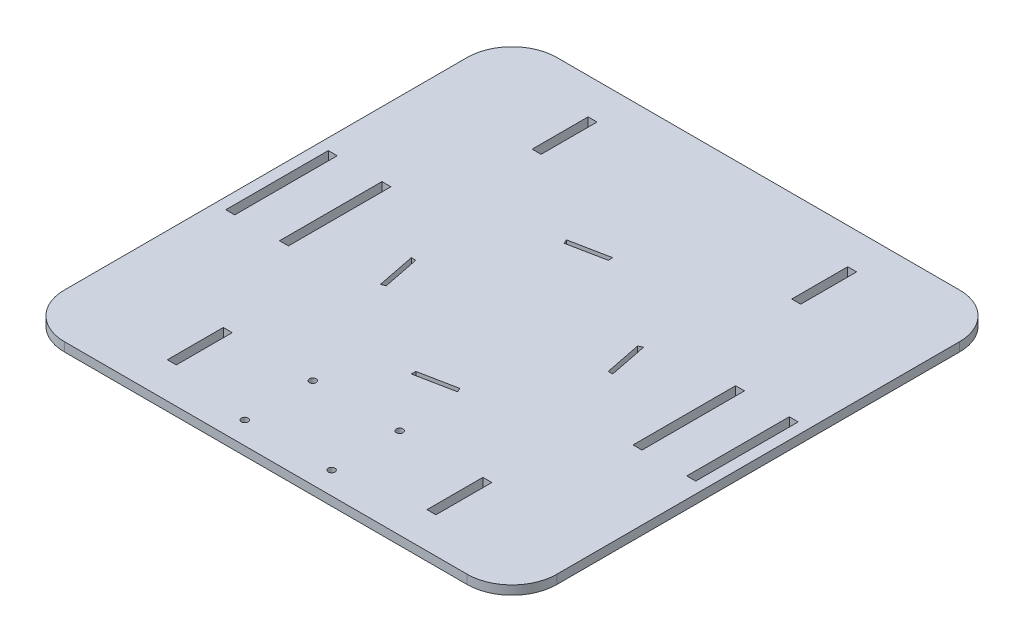
SolidWorks part; units mm, degrees
ref_plane "Front Plane" through (0, 0, 0) normal (0, 0, 1) x (1, 0, 0)
ref_plane "Top Plane" through (0, 0, 0) normal (0, 1, 0) x (1, 0, 0)
ref_plane "Right Plane" through (0, 0, 0) normal (1, 0, 0) x (0, 0, -1)
sketch "Sketch1" plane through (0, 0, 0) normal (0, 1, 0) x (1, 0, 0)
  line L1 (0, 0) -> (279.4, 0)
  line L2 (0, 0) -> (0, 279.4)
  line L3 (0, 279.4) -> (279.4, 279.4)
  line L4 (279.4, 0) -> (279.4, 279.4)
  dimension "D1" = 279.4
  dimension "D2" = 279.4
extrude "Boss-Extrude1" add sketch "Sketch1" along normal blind 5.08
fillet "Fillet1" radius 25.4 4 edges at (0, 2.54, -279.4) (0, 2.54, 0) (279.4, 2.54, 0) (279.4, 2.54, -279.4)
sketch "Sketch2" plane through (0, 5.08, 0) normal (0, 1, 0) x (1, 0, 0)
  line L0 (254, 279.4) -> (25.4, 279.4) construction
  line L1 (63.5, 259.08) -> (68.58, 259.08)
  line L2 (63.5, 259.08) -> (63.5, 227.33)
  line L3 (63.5, 227.33) -> (68.58, 227.33)
  line L4 (68.58, 259.08) -> (68.58, 227.33)
  line L5 (210.82, 259.08) -> (215.9, 259.08)
  line L6 (210.82, 259.08) -> (210.82, 227.33)
  line L7 (210.82, 227.33) -> (215.9, 227.33)
  line L8 (215.9, 259.08) -> (215.9, 227.33)
  line L9 (63.5, 52.07) -> (68.58, 52.07)
  line L10 (63.5, 52.07) -> (63.5, 20.32)
  line L11 (63.5, 20.32) -> (68.58, 20.32)
  line L12 (68.58, 52.07) -> (68.58, 20.32)
  line L13 (210.82, 52.07) -> (215.9, 52.07)
  line L14 (210.82, 52.07) -> (210.82, 20.32)
  line L15 (210.82, 20.32) -> (215.9, 20.32)
  line L16 (215.9, 52.07) -> (215.9, 20.32)
  line L17 (25.4, 0) -> (254, 0) construction
  line L18 (0, 254) -> (0, 25.4) construction
  line L19 (279.4, 25.4) -> (279.4, 254) construction
  point P18 (66.04, 20.32)
  dimension "D1" = 5.08
  dimension "D2" = 5.08
  dimension "D3" = 5.08
  dimension "D4" = 5.08
  dimension "D5" = 20.32
  dimension "D6" = 20.32
  dimension "D7" = 20.32
  dimension "D8" = 20.32
  dimension "D9" = 31.75
  dimension "D10" = 31.75
  dimension "D11" = 31.75
  dimension "D12" = 31.75
  dimension "D13" = 63.5
  dimension "D14" = 63.5
  dimension "D15" = 63.5
  dimension "D16" = 63.5
extrude "Cut-Extrude1" cut sketch "Sketch2" against normal through all
sketch "Sketch3" plane through (0, 5.08, 0) normal (0, 1, 0) x (1, 0, 0)
  line L0 (279.4, 25.4) -> (279.4, 254) construction
  line L1 (6.35, 168.783) -> (11.43, 168.783)
  line L2 (6.35, 168.783) -> (6.35, 110.617)
  line L3 (6.35, 110.617) -> (11.43, 110.617)
  line L4 (11.43, 168.783) -> (11.43, 110.617)
  line L5 (267.97, 168.783) -> (273.05, 168.783)
  line L6 (267.97, 168.783) -> (267.97, 110.617)
  line L7 (267.97, 110.617) -> (273.05, 110.617)
  line L8 (273.05, 168.783) -> (273.05, 110.617)
  line L9 (36.83, 168.783) -> (41.91, 168.783)
  line L10 (36.83, 168.783) -> (36.83, 110.617)
  line L11 (36.83, 110.617) -> (41.91, 110.617)
  line L12 (41.91, 168.783) -> (41.91, 110.617)
  line L13 (237.49, 168.783) -> (242.57, 168.783)
  line L14 (237.49, 168.783) -> (237.49, 110.617)
  line L15 (237.49, 110.617) -> (242.57, 110.617)
  line L16 (242.57, 168.783) -> (242.57, 110.617)
  line L17 (0, 254) -> (0, 25.4) construction
  line L18 (254, 279.4) -> (25.4, 279.4) construction
  point P20 (8.89, 110.617)
  dimension "D1" = 5.08
  dimension "D2" = 5.08
  dimension "D3" = 5.08
  dimension "D4" = 5.08
  dimension "D5" = 25.4
  dimension "D6" = 25.4
  dimension "D7" = 6.35
  dimension "D8" = 6.35
  dimension "D9" = 58.166
  dimension "D10" = 58.166
  dimension "D11" = 58.166
  dimension "D12" = 58.166
  dimension "D13" = 110.617
  dimension "D14" = 110.617
  dimension "D15" = 110.617
  dimension "D16" = 110.617
extrude "Cut-Extrude2" cut sketch "Sketch3" against normal through all
sketch "Sketch5" plane through (0, 0, 0) normal (0, -1, 0) x (1, 0, 0)
  line L0 (25.4, 0) -> (254, 0) construction
  line L1 (0, -254) -> (0, -25.4) construction
  circle A0 centre (115.062, -12.7) radius 1.905
  circle A1 centre (164.338, -12.7) radius 1.905
  circle A2 centre (164.338, -51.308) radius 1.905
  circle A3 centre (115.062, -51.308) radius 1.905
  dimension "D1" = 3.81
  dimension "D2" = 3.81
  dimension "D3" = 3.81
  dimension "D4" = 3.81
  dimension "D5" = 49.276
  dimension "D6" = 49.276
  dimension "D7" = 38.608
  dimension "D8" = 12.7
  dimension "D9" = 12.7
  dimension "D10" = 38.608
  dimension "D11" = 115.062
  dimension "D12" = 115.062
extrude "Cut-Extrude4" cut sketch "Sketch5" against normal through all
sketch "Sketch6" plane through (0, 5.08, 0) normal (0, 1, 0) x (1, 0, 0)
  line L10 (117.8296, 192.4997) -> (118.8017, 190.1531)
  line L43 (118.8017, 190.1531) -> (139.7, 194.31)
  line L58 (139.7, 194.31) -> (139.7, 196.85)
  line L75 (139.7, 196.85) -> (117.8296, 192.4997)
  line L76 (254, 279.4) -> (25.4, 279.4) construction
  line L93 (139.7, 196.85) -> (117.8296, 192.4997) construction
  line L94 (117.8296, 192.4997) -> (99.2888, 180.1112) construction
  line L95 (99.2888, 180.1112) -> (86.9003, 161.5704) construction
  line L96 (86.9003, 161.5704) -> (82.55, 139.7) construction
  line L97 (82.55, 139.7) -> (86.9003, 117.8296) construction
  line L98 (86.9003, 117.8296) -> (99.2888, 99.2888) construction
  line L99 (99.2888, 99.2888) -> (117.8296, 86.9003) construction
  line L100 (117.8296, 86.9003) -> (139.7, 82.55) construction
  line L101 (139.7, 82.55) -> (161.5704, 86.9003) construction
  line L102 (161.5704, 86.9003) -> (180.1112, 99.2888) construction
  line L103 (180.1112, 99.2888) -> (192.4997, 117.8296) construction
  line L104 (192.4997, 117.8296) -> (196.85, 139.7) construction
  line L105 (196.85, 139.7) -> (192.4997, 161.5704) construction
  line L106 (192.4997, 161.5704) -> (180.1112, 180.1112) construction
  line L107 (180.1112, 180.1112) -> (161.5704, 192.4997) construction
  line L108 (161.5704, 192.4997) -> (139.7, 196.85) construction
  line L109 (0, 254) -> (0, 25.4) construction
  line L110 (82.55, 139.7) -> (86.9003, 117.8296)
  line L111 (139.7, 194.31) -> (118.8017, 190.1531) construction
  line L112 (118.8017, 190.1531) -> (101.0849, 178.3151) construction
  line L113 (101.0849, 178.3151) -> (89.2469, 160.5983) construction
  line L114 (89.2469, 160.5983) -> (85.09, 139.7) construction
  line L115 (85.09, 139.7) -> (89.2469, 118.8017) construction
  line L116 (89.2469, 118.8017) -> (101.0849, 101.0849) construction
  line L117 (101.0849, 101.0849) -> (118.8017, 89.2469) construction
  line L118 (118.8017, 89.2469) -> (139.7, 85.09) construction
  line L119 (139.7, 85.09) -> (160.5983, 89.2469) construction
  line L120 (160.5983, 89.2469) -> (178.3151, 101.0849) construction
  line L121 (178.3151, 101.0849) -> (190.1531, 118.8017) construction
  line L122 (190.1531, 118.8017) -> (194.31, 139.7) construction
  line L123 (194.31, 139.7) -> (190.1531, 160.5983) construction
  line L124 (190.1531, 160.5983) -> (178.3151, 178.3151) construction
  line L125 (178.3151, 178.3151) -> (160.5983, 190.1531) construction
  line L126 (160.5983, 190.1531) -> (139.7, 194.31) construction
  line L127 (86.9003, 117.8296) -> (89.2469, 118.8017)
  line L128 (89.2469, 118.8017) -> (85.09, 139.7)
  line L129 (85.09, 139.7) -> (82.55, 139.7)
  line L130 (160.5983, 89.2469) -> (161.5704, 86.9003)
  line L131 (161.5704, 86.9003) -> (139.7, 82.55)
  line L132 (139.7, 82.55) -> (139.7, 85.09)
  line L133 (139.7, 85.09) -> (160.5983, 89.2469)
  line L134 (196.85, 139.7) -> (192.4997, 161.5704)
  line L135 (192.4997, 161.5704) -> (190.1531, 160.5983)
  line L136 (190.1531, 160.5983) -> (194.31, 139.7)
  line L137 (194.31, 139.7) -> (196.85, 139.7)
  circle A13 centre (139.7, 139.7) radius 56.0519 construction
  circle A14 centre (139.7, 139.7) radius 53.5607 construction
  dimension "D1" = 114.3
  dimension "D2" = 139.7
  dimension "D3" = 139.7
  dimension "D4" = 2.54
extrude "Cut-Extrude6" cut sketch "Sketch6" against normal through all contours L133 L130 L131 L132 | L43 L58 L75 L10 | L128 L129 L110 L127 | L136 L137 L134 L135
equation "\"MDF\"= .2"
equation "\"Foamcore\"= .1"
equation "\"GMaterial\"= \"MDF\""
equation "\"D1@Boss-Extrude1\"=\"GMaterial\""
equation "\"D2@Sketch2\"=\"GMaterial\""
equation "\"D1@Sketch2\"=\"GMaterial\""
equation "\"D4@Sketch2\"=\"GMaterial\""
equation "\"D3@Sketch2\"=\"GMaterial\""
equation "\"D3@Sketch3\"=\"GMaterial\""
equation "\"D4@Sketch3\"=\"GMaterial\""
equation "\"D2@Sketch3\"=\"GMaterial\""
equation "\"D1@Sketch3\"=\"GMaterial\""
equation "\"D4@Sketch6\"=\"Foamcore\""
